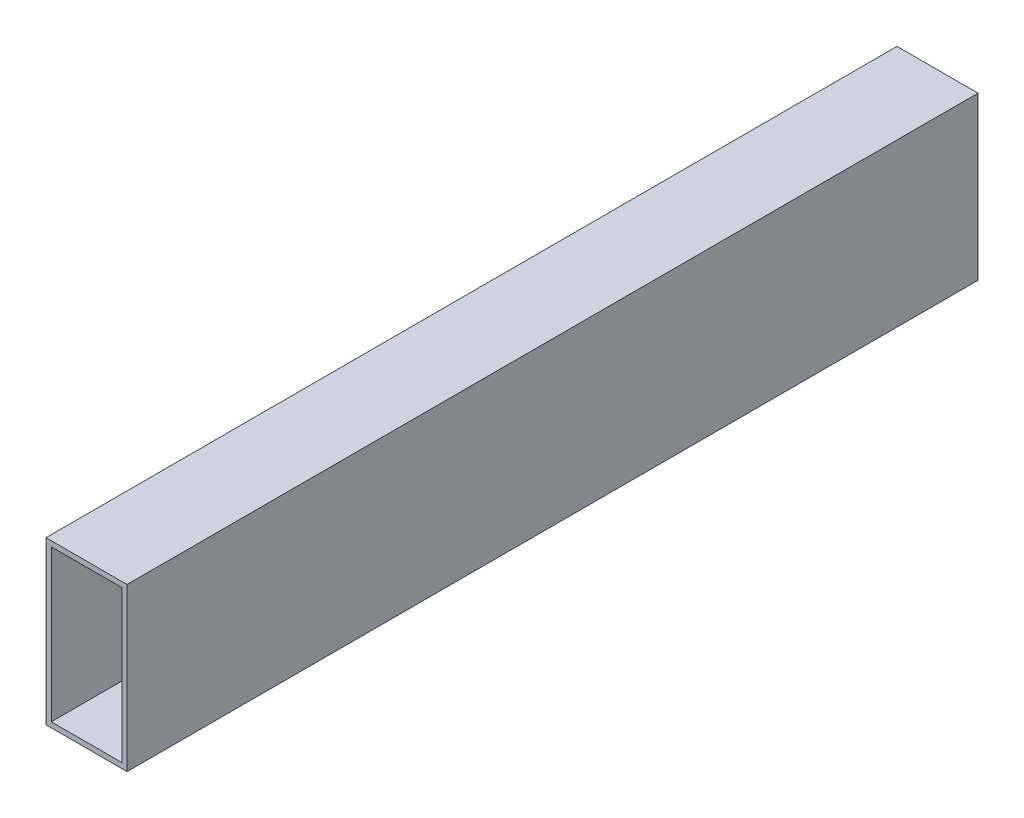
SolidWorks part; units mm, degrees
ref_plane "Front Plane" through (0, 0, 0) normal (0, 0, 1) x (1, 0, 0)
ref_plane "Top Plane" through (0, 0, 0) normal (0, 1, 0) x (1, 0, 0)
ref_plane "Right Plane" through (0, 0, 0) normal (1, 0, 0) x (0, 0, -1)
sketch "Sketch1" plane through (0, 0, 0) normal (0, 0, 1) x (1, 0, 0)
  line L1 (-52.8767, -32.8283) -> (-27.4767, -32.8283)
  line L2 (-52.8767, -32.8283) -> (-52.8767, 17.9717)
  line L3 (-52.8767, 17.9717) -> (-27.4767, 17.9717)
  line L4 (-27.4767, -32.8283) -> (-27.4767, 17.9717)
  dimension "D1" = 25.4
  dimension "D2" = 50.8
extrude "Boss-Extrude1" add sketch "Sketch1" along normal blind 266.7
sketch "Sketch2" plane through (0, 0, 266.7) normal (0, 0, 1) x (1, 0, 0)
  line L0 (-52.8767, 17.9717) -> (-52.8767, -32.8283) construction
  line L1 (-51.2257, 16.3207) -> (-29.1277, 16.3207)
  line L2 (-51.2257, 16.3207) -> (-51.2257, -31.1773)
  line L3 (-51.2257, -31.1773) -> (-29.1277, -31.1773)
  line L4 (-29.1277, 16.3207) -> (-29.1277, -31.1773)
  line L5 (-51.2257, 16.3207) -> (-29.1277, -31.1773) construction
  line L6 (-51.2257, -31.1773) -> (-29.1277, 16.3207) construction
  line L7 (-27.4767, 17.9717) -> (-52.8767, 17.9717) construction
  line L8 (-27.4767, -32.8283) -> (-27.4767, 17.9717) construction
  line L9 (-52.8767, -32.8283) -> (-27.4767, -32.8283) construction
  point P0 (-40.1767, -7.4283)
  dimension "D1" = 1.651
  dimension "D2" = 1.651
  dimension "D3" = 1.651
  dimension "D4" = 1.651
extrude "Cut-Extrude1" cut sketch "Sketch2" against normal through all
